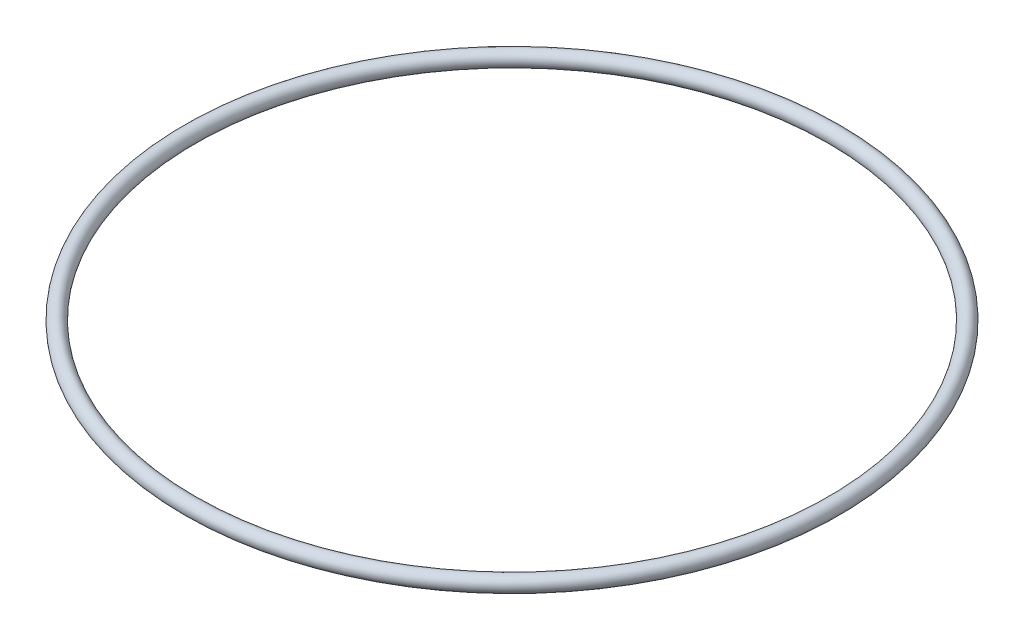
SolidWorks part; units mm, degrees
ref_plane "Płaszczyzna przednia" through (0, 0, 0) normal (0, 0, 1) x (1, 0, 0)
ref_plane "Płaszczyzna górna" through (0, 0, 0) normal (0, 1, 0) x (1, 0, 0)
ref_plane "Płaszczyzna prawa" through (0, 0, 0) normal (1, 0, 0) x (0, 0, -1)
sketch "Szkic1" plane through (0, 0, 0) normal (0, 0, 1) x (1, 0, 0)
  line L0 (0, 16.1857) -> (0, -14.02) construction
  circle A0 centre (-63.5, 0) radius 1.5
  dimension "D1" = 3
  dimension "D2" = 63.5
revolve "Obrót1" add sketch "Szkic1" angle 360 about L0
